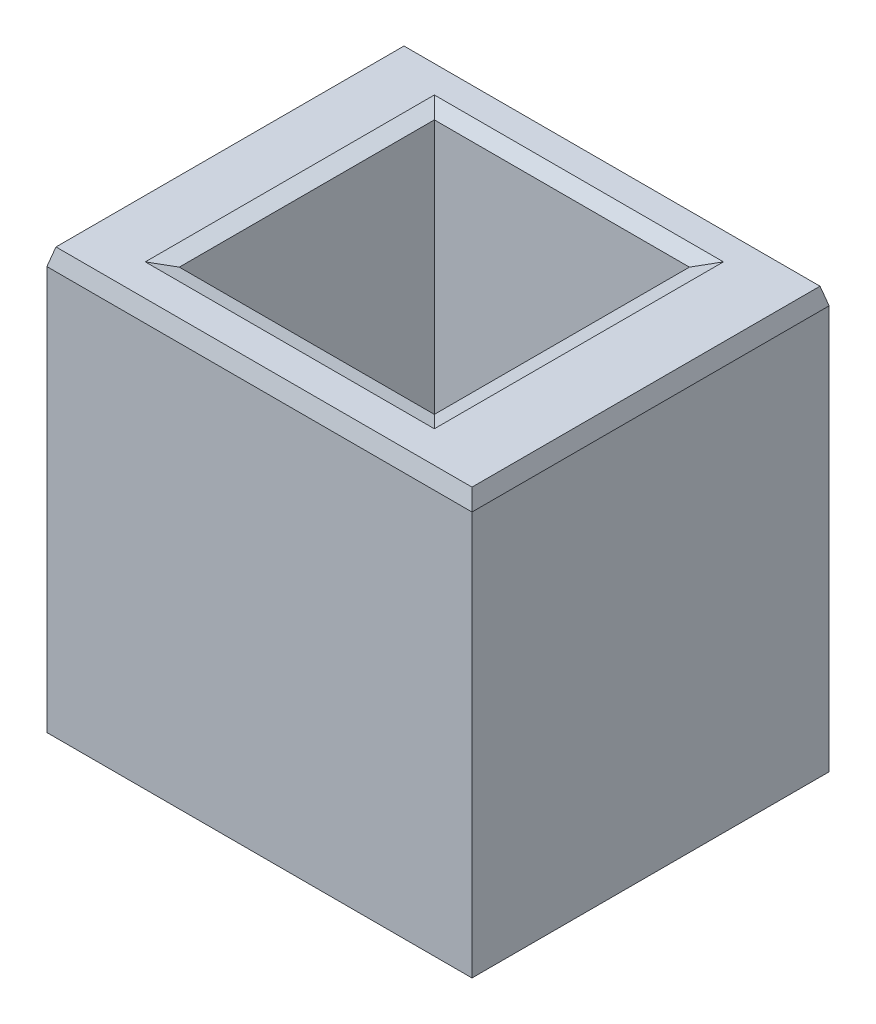
SolidWorks part; units mm, degrees
ref_plane "Front Plane" through (0, 0, 0) normal (0, 0, 1) x (1, 0, 0)
ref_plane "Top Plane" through (0, 0, 0) normal (0, 1, 0) x (1, 0, 0)
ref_plane "Right Plane" through (0, 0, 0) normal (1, 0, 0) x (0, 0, -1)
sketch "Sketch1" plane through (0, 0, 0) normal (0, 1, 0) x (1, 0, 0)
  line L1 (-58.2196, 28.5682) -> (68.7804, 28.5682)
  line L2 (-58.2196, 28.5682) -> (-58.2196, -78.1226)
  line L3 (-58.2196, -78.1226) -> (68.7804, -78.1226)
  line L4 (68.7804, 28.5682) -> (68.7804, -78.1226)
  dimension "D1" = 127
extrude "Boss-Extrude1" add sketch "Sketch1" along normal blind 127
sketch "Sketch3" plane through (0, 0, 0) normal (0, 1, 0) x (1, 0, 0)
  line L1 (-34.576, 13.9931) -> (41.624, 13.9931)
  line L2 (-34.576, 13.9931) -> (-34.576, -62.2069)
  line L3 (-34.576, -62.2069) -> (41.624, -62.2069)
  line L4 (41.624, 13.9931) -> (41.624, -62.2069)
  line L5 (-34.576, 13.9931) -> (41.624, -62.2069) construction
  line L6 (-34.576, -62.2069) -> (41.624, 13.9931) construction
  point P0 (3.524, -24.1069)
  dimension "D1" = 76.2
extrude "Cut-Extrude1" cut sketch "Sketch3" along normal through all
chamfer "Chamfer1" distance 5.08 angle 15 16 edges at (3.524, 0, 62.2069) (-34.576, 0, 24.1069) (3.524, 0, -13.9931) (41.624, 0, 24.1069) (5.2804, 0, 78.1226) (68.7804, 0, 24.7772) (5.2804, 0, -28.5682) (-58.2196, 0, 24.7772) (-34.576, 127, 24.1069) (3.524, 127, 62.2069) (41.624, 127, 24.1069) (3.524, 127, -13.9931) (5.2804, 127, -28.5682) (68.7804, 127, 24.7772) (5.2804, 127, 78.1226) (-58.2196, 127, 24.7772)
